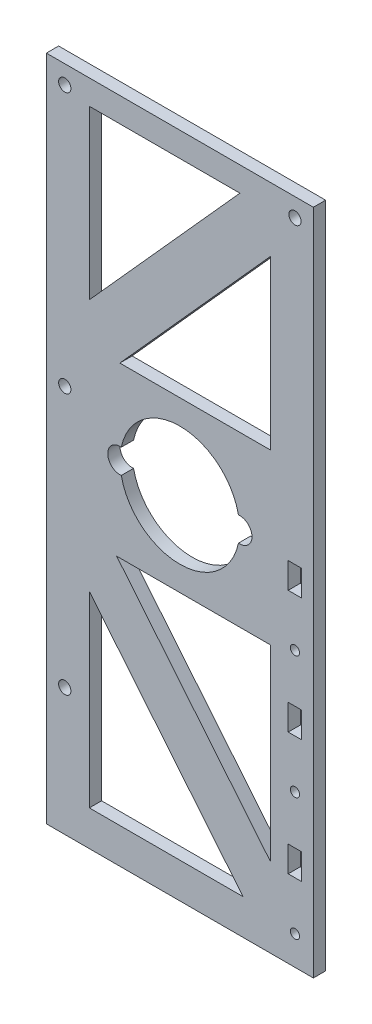
SolidWorks part; units mm, degrees
ref_plane "前视基准面" through (0, 0, 0) normal (0, 0, 1) x (1, 0, 0)
ref_plane "上视基准面" through (0, 0, 0) normal (0, 1, 0) x (1, 0, 0)
ref_plane "右视基准面" through (0, 0, 0) normal (1, 0, 0) x (0, 0, -1)
sketch "草图1" plane through (0, 0, 0) normal (0, 0, 1) x (1, 0, 0)
  line L0 (0, 20) -> (37.5, 20) construction
  line L1 (-37.5, 50) -> (37.5, 50)
  line L2 (-37.5, 50) -> (-37.5, -164) construction
  line L3 (-37.5, -164) -> (37.5, -164)
  line L4 (37.5, 50) -> (37.5, -164) construction
  line L5 (0, 20) -> (-37.5, 20) construction
  line L6 (37.5, -57) -> (43.5, -57) construction
  line L7 (43.5, -57) -> (43.5, -164)
  line L8 (43.5, -164) -> (37.5, -164)
  line L9 (-37.5, -57) -> (-43.5, -57) construction
  line L10 (-43.5, -57) -> (-43.5, -164)
  line L11 (-43.5, -164) -> (-37.5, -164)
  line L12 (-37.5, 50) -> (-37.5, -57) construction
  line L13 (37.5, -57) -> (37.5, 50) construction
  line L14 (-43.5, -57) -> (-43.5, 50)
  line L15 (-43.5, 50) -> (-37.5, 50)
  line L16 (43.5, -57) -> (43.5, 50)
  line L17 (43.5, 50) -> (37.5, 50)
  line L18 (0, 0) -> (0, -53) construction
  line L19 (0, -72.5) -> (-43.5, -72.5) construction
  line L20 (-37.5, -72.5) -> (37.5, -164) construction
  line L21 (-37.5, -72.5) -> (37.5, -72.5) construction
  line L22 (37.5, -72.5) -> (37.5, -164) construction
  line L23 (29.5, -80.5) -> (29.5, -141.6203)
  line L24 (-20.5986, -80.5) -> (29.5, -80.5)
  line L25 (-20.5986, -80.5) -> (29.5, -141.6203)
  line L26 (-37.5, -72.5) -> (-37.5, -164) construction
  line L27 (-29.5, -94.8797) -> (20.5986, -156)
  line L28 (-29.5, -156) -> (20.5986, -156)
  line L29 (-29.5, -94.8797) -> (-29.5, -156)
  line L30 (37.5, 50) -> (-37.5, -33.5) construction
  line L31 (-37.5, -33.5) -> (37.5, -33.5) construction
  line L32 (37.5, -33.5) -> (37.5, 50) construction
  line L33 (29.5, 29.1213) -> (-19.5611, -25.5)
  line L34 (-19.5611, -25.5) -> (29.5, -25.5)
  line L35 (29.5, -25.5) -> (29.5, 29.1213)
  line L36 (-37.5, -33.5) -> (-37.5, 50) construction
  line L37 (19.5611, 42) -> (-29.5, -12.6213)
  line L38 (-29.5, -12.6213) -> (-29.5, 42)
  line L39 (-29.5, 42) -> (19.5611, 42)
  circle A9 centre (0, -53) radius 19.5 construction
  circle A10 centre (19.5, -53) radius 4 construction
  circle A11 centre (-19.5, -53) radius 4 construction
  arc A12 (19.0897, -49.0211) -> (-19.0897, -49.0211) centre (0, -53) ccw
  arc A13 (19.0897, -56.9789) -> (-19.0897, -56.9789) centre (0, -53) cw
  arc A14 (19.0897, -49.0211) -> (19.0897, -56.9789) centre (19.5, -53) cw
  arc A15 (-19.0897, -49.0211) -> (-19.0897, -56.9789) centre (-19.5, -53) ccw
  dimension "D4" = 8
  dimension "D12" = 8
  dimension "D2" = 20
  dimension "D3" = 8
  dimension "D6" = 37.5
  dimension "D7" = 214
  dimension "D11" = 6
  dimension "D13" = 8
extrude "凸台-拉伸1" add sketch "草图1" along normal blind 4 contours L3 L4 L1 L2
sketch "草图2" plane through (0, 0, 4) normal (0, 0, 1) x (1, 0, 0)
  line L0 (37.5, -78) -> (37.5, -158) construction
  line L2 (43.5, -164) -> (37.5, -158) construction
  line L4 (35.3, -133.8) -> (39.7, -133.8)
  line L9 (-43.5, -164) -> (43.5, -164) construction
  line L10 (43.5, 50) -> (-43.5, 50) construction
  line L11 (35.3, -133.8) -> (35.3, -142.2)
  line L16 (0, 0) -> (0, -38.3122) construction
  line L20 (-37.5, -64) -> (-37.5, -145.909) construction
  line L21 (35.3, -142.2) -> (39.7, -142.2)
  line L22 (39.7, -133.8) -> (39.7, -142.2)
  line L23 (35.3, -133.8) -> (39.7, -142.2) construction
  line L24 (35.3, -142.2) -> (39.7, -133.8) construction
  line L25 (39.7, -102.2) -> (39.7, -93.8)
  line L26 (35.3, -93.8) -> (39.7, -93.8)
  line L27 (35.3, -102.2) -> (35.3, -93.8)
  line L28 (35.3, -102.2) -> (39.7, -102.2)
  line L29 (37.5, -78) -> (40.1693, -78) construction
  line L30 (35.3, -62.2) -> (39.7, -62.2)
  line L31 (35.3, -53.8) -> (35.3, -62.2)
  line L32 (35.3, -53.8) -> (39.7, -53.8)
  line L33 (39.7, -53.8) -> (39.7, -62.2)
  line L35 (43.5, -164) -> (43.5, 50) construction
  circle A2 centre (37.5, -158) radius 1.5
  circle A3 centre (37.5, -78) radius 1.5
  circle A4 centre (37.5, -118) radius 1.5
  circle A5 centre (37.5, 44) radius 2
  circle A6 centre (-37.5, 44) radius 2
  circle A7 centre (-37.5, -41) radius 2
  circle A8 centre (-37.5, -126) radius 2
  point P3 (37.5, -138)
  dimension "D2" = 6
  dimension "D5" = 3
  dimension "D3" = 6
  dimension "D1" = 6
  dimension "D4" = 6
extrude "切除-拉伸1" cut sketch "草图2" against normal blind 4
sketch "草图3" plane through (0, 0, 4) normal (0, 0, 1) x (1, 0, 0)
  line L1 (-43.5, -164) -> (43.5, -164)
  line L2 (-43.5, -164) -> (-43.5, -167.5)
  line L3 (-43.5, -167.5) -> (43.5, -167.5)
  line L4 (43.5, -164) -> (43.5, -167.5)
extrude "凸台-拉伸2" add sketch "草图3" against normal blind 4
